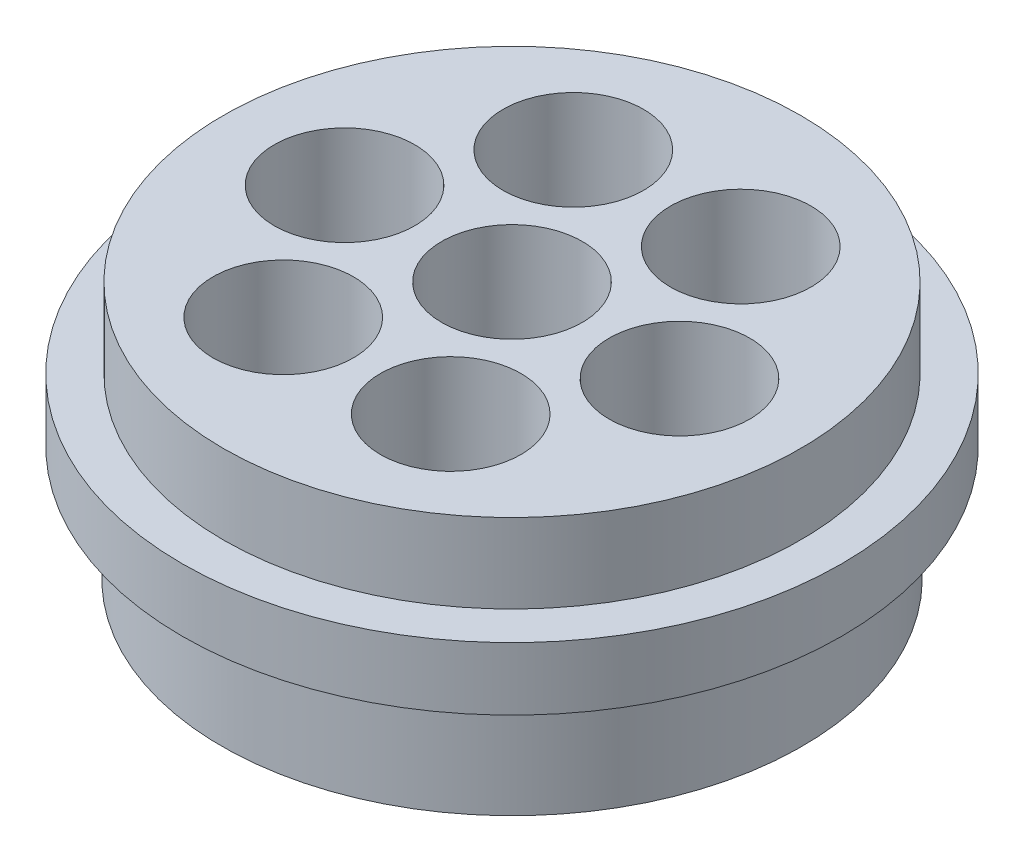
SolidWorks part; units mm, degrees
ref_plane "Front Plane" through (0, 0, 0) normal (0, 0, 1) x (1, 0, 0)
ref_plane "Top Plane" through (0, 0, 0) normal (0, 1, 0) x (1, 0, 0)
ref_plane "Right Plane" through (0, 0, 0) normal (1, 0, 0) x (0, 0, -1)
sketch "Croquis4" plane through (0, 0, 0) normal (0, 1, 0) x (1, 0, 0)
  circle A0 centre (0, 0) radius 9.7
  dimension "D1" = 19.4
extrude "Saliente-Extruir2" add sketch "Croquis4" along normal blind 3.85
sketch "Croquis5" plane through (0, 3.85, 0) normal (0, 1, 0) x (1, 0, 0)
  circle A0 centre (0, 0) radius 11.025
  dimension "D1" = 22.05
extrude "Saliente-Extruir3" add sketch "Croquis5" along normal blind 2.1
sketch "Croquis6" plane through (0, 5.95, 0) normal (0, 1, 0) x (1, 0, 0)
  circle A0 centre (0, 0) radius 9.65
  dimension "D1" = 19.3
extrude "Saliente-Extruir4" add sketch "Croquis6" along normal blind 2.65
sketch "Croquis8" plane through (0, 0, 0) normal (0, -1, 0) x (1, 0, 0)
  circle A1 centre (0, 0) radius 8.725
  dimension "D2" = 17.45
extrude "Cortar-Extruir2" cut sketch "Croquis8" against normal blind 4.05
sketch "Croquis9" plane through (0, 8.6, 0) normal (0, 1, 0) x (1, 0, 0)
  line L0 (0, 0) -> (-4.825, 8.3571) construction
  line L7 (0, 0) -> (4.825, 8.3571) construction
  line L8 (0, 0) -> (9.65, 0) construction
  line L9 (0, 0) -> (4.825, -8.3571) construction
  line L10 (4.825, -8.3571) -> (0, 0) construction
  line L11 (0, 0) -> (-4.825, -8.3571) construction
  line L12 (0, 0) -> (-9.65, 0) construction
  circle A0 centre (0, 0) radius 9.65 construction
  circle A1 centre (-2.8, 4.8497) radius 2.35
  circle A2 centre (5.6, 0) radius 2.35
  circle A3 centre (0, 0) radius 9.65 construction
  circle A4 centre (0, 0) radius 2.35
  circle A5 centre (2.8, 4.8497) radius 2.35
  circle A6 centre (2.8, -4.8497) radius 2.35
  circle A7 centre (-2.8, -4.8498) radius 2.35
  circle A8 centre (-5.6, 0) radius 2.35
  point P10 (7.95, 0)
  point P23 (-3.975, 6.8849)
  point P24 (3.975, -6.8849)
  point P25 (3.975, 6.8849)
  point P28 (-3.9695, -6.8881)
  point P31 (-7.95, 0)
  point P33 (2.8, 4.8497)
  dimension "D1" = 4.7
  dimension "D5" = 4.7
  dimension "D6" = 4.7
  dimension "D7" = 4.7
  dimension "D8" = 4.7
  dimension "D9" = 4.7
  dimension "D10" = 4.7
  dimension "D2" = 60
  dimension "D3" = 60
  dimension "D4" = 1.7
  dimension "D11" = 1.7
  dimension "D12" = 1.7
  dimension "D13" = 1.7
  dimension "D14" = 1.7
  dimension "D15" = 1.7
extrude "Cortar-Extruir3" cut sketch "Croquis9" against normal up to surface (4.55 mm away) up to face at (0, 4.05, -8.725)
sketch "Croquis10" plane through (0, 4.05, 0) normal (0, -1, 0) x (1, 0, 0)
  line L0 (0, 9.7) -> (0, -9.7) construction
  line L1 (8.4004, -4.85) -> (-8.4004, 4.85) construction
  line L2 (0, 0) -> (-8.4004, -4.85) construction
  line L3 (0, 0) -> (8.4004, 4.85) construction
  circle A0 centre (0, 8.3) radius 1.2
  circle A1 centre (0, 0) radius 9.7 construction
  circle A2 centre (0, 0) radius 9.7 construction
  circle A4 centre (-7.188, 4.15) radius 1.2
  circle A5 centre (-7.188, -4.15) radius 1.2
  circle A6 centre (0, -8.3) radius 1.2
  circle A7 centre (7.188, -4.15) radius 1.2
  circle A8 centre (7.188, 4.15) radius 1.2
  point P11 (0, 7.1)
  point P17 (0, 0)
  point P18 (-6.1488, 3.55)
  point P21 (-6.1488, -3.55)
  point P33 (0, -7.1)
  point P34 (6.1488, -3.55)
  point P35 (6.1488, 3.55)
  dimension "D1" = 2.4
  dimension "D6" = 2.4
  dimension "D8" = 2.4
  dimension "D10" = 2.4
  dimension "D11" = 2.4
  dimension "D12" = 2.4
  dimension "D2" = 2.6
  dimension "D3" = 60
  dimension "D4" = 60
  dimension "D5" = 60
  dimension "D7" = 2.6
  dimension "D9" = 2.6
  dimension "D13" = 2.6
  dimension "D14" = 2.6
  dimension "D15" = 2.6
extrude "Saliente-Extruir5" add sketch "Croquis10" along normal up to surface (4.05 mm away) up to face at (0, 0, -8.725)
